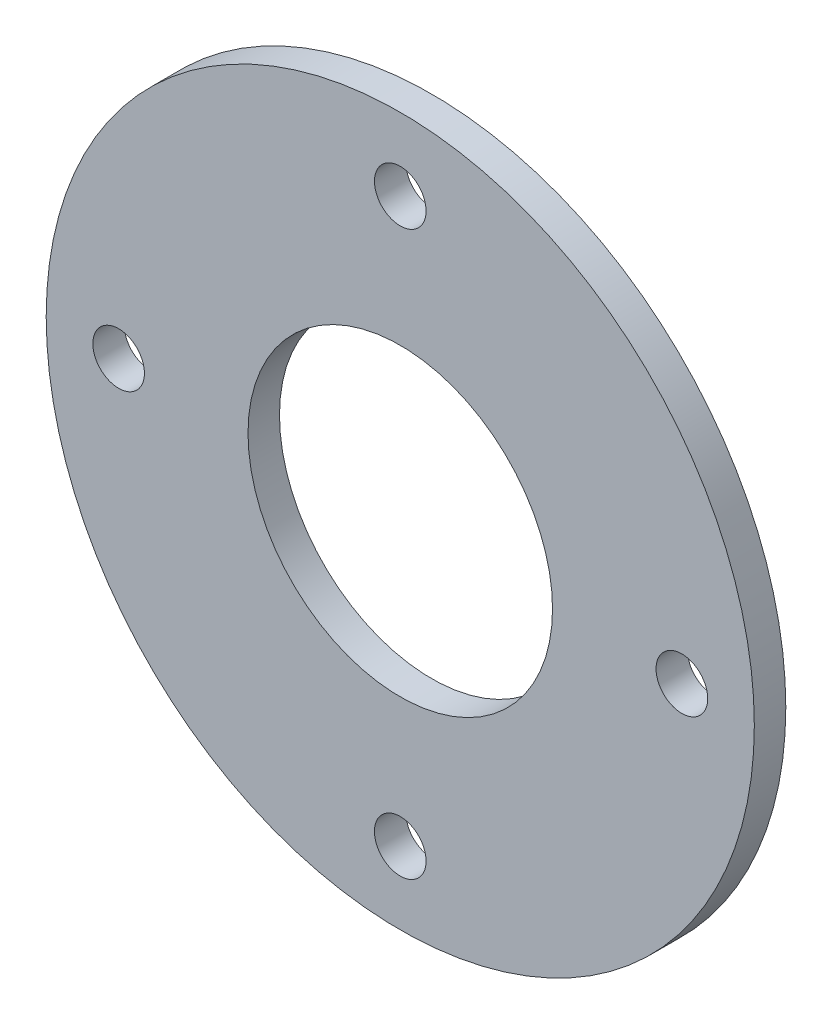
SolidWorks part; units mm, degrees
material "AISI 1020"
ref_plane "Front Plane" through (0, 0, 0) normal (0, 0, 1) x (1, 0, 0)
ref_plane "Top Plane" through (0, 0, 0) normal (0, 1, 0) x (1, 0, 0)
ref_plane "Right Plane" through (0, 0, 0) normal (1, 0, 0) x (0, 0, -1)
other "Configuration Table"
sketch "Sketch1" plane through (0, 0, 0) normal (0, 0, 1) x (1, 0, 0)
  circle A10 centre (0, 0) radius 114.3
  circle A11 centre (0, 0) radius 49.15
extrude "Extrude1" add sketch "Sketch1" along normal blind 10.16
hole_wizard "5/8 Clearance Hole1" positions "Sketch2" profile "Sketch3" hole size "5/8" standard "Ansi Inch" end condition through all
sketch "Sketch2" plane through (-61.2299, -86.9453, 0) normal (0, 0, -1) x (-1, 0, 0)
  line L0 (-61.2299, 86.9453) -> (160.2598, 86.9453) construction
  line L1 (-61.2299, 86.9453) -> (-61.2299, 296.6144) construction
  line L2 (-61.2299, 86.9453) -> (-291.9631, 86.9453) construction
  line L3 (-61.2299, 86.9453) -> (-61.2299, -121.1078) construction
  circle A0 centre (-61.2299, 86.9453) radius 90.9114 construction
  point P0 (-61.2299, 177.798)
  point P1 (29.6815, 86.9453)
  point P2 (-61.2299, -3.9661)
  point P3 (-152.1413, 86.9453)
sketch "Sketch3" plane through (0, 90.8528, 0) normal (1, 0, 0) x (0, 1, 0)
  line L0 (0, 0) -> (0, 10.16)
  line L1 (0, 10.16) -> (8.3337, 10.16)
  line L2 (8.3337, 10.16) -> (8.3337, 0)
  line L5 (8.3337, 0) -> (0, 0)
  line L11 (0, -6.35) -> (0, 107.95) construction
  dimension "Thru Hole Dia." = 16.6675
  dimension "Thru Hole Depth" = 10.16
